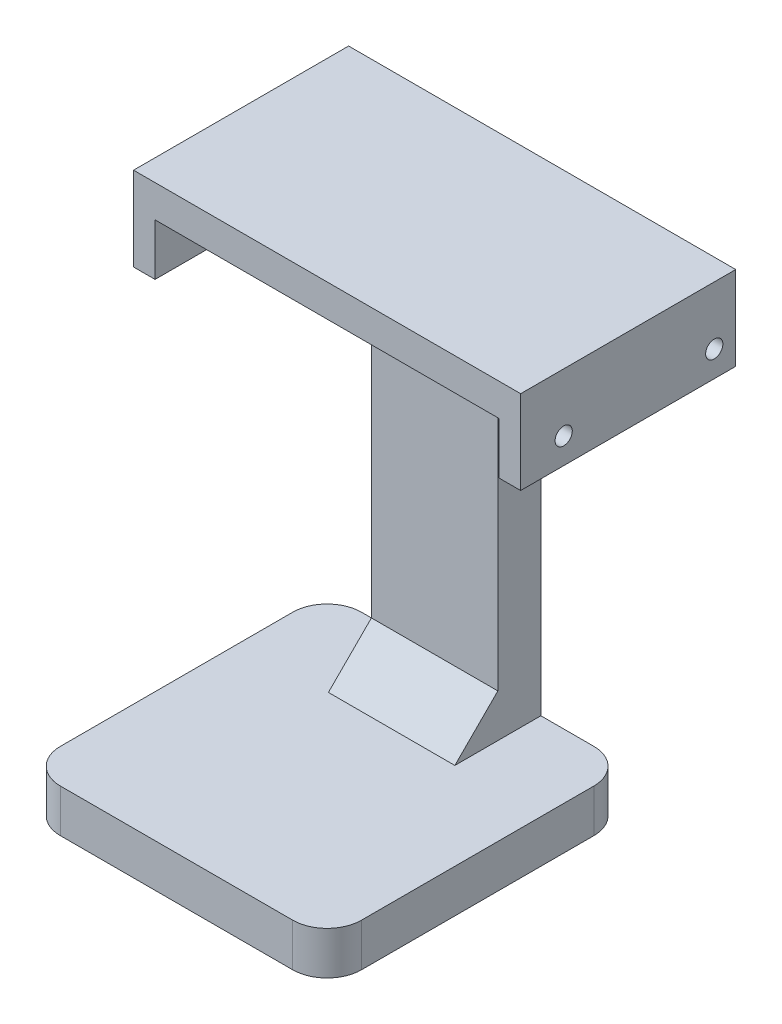
SolidWorks part; units mm, degrees
ref_plane "前视基准面" through (0, 0, 0) normal (0, 0, 1) x (1, 0, 0)
ref_plane "上视基准面" through (0, 0, 0) normal (0, 1, 0) x (1, 0, 0)
ref_plane "右视基准面" through (0, 0, 0) normal (1, 0, 0) x (0, 0, -1)
other "Configuration Table"
sketch "草图2" plane through (0, 0, 0) normal (0, 0, 1) x (1, 0, 0)
  line L0 (0, 48.4771) -> (0, -25.8756) construction
  line L1 (-45, 7.5) -> (45, 7.5)
  line L2 (45, 7.5) -> (45, -12)
  line L3 (45, -12) -> (40, -12)
  line L4 (40, -12) -> (40, 0)
  line L5 (40, 0) -> (14.7, 0)
  line L6 (14.7, 0) -> (14.7, -100)
  line L7 (14.7, -100) -> (-14.7, -100)
  line L8 (-14.7, 0) -> (-14.7, -100)
  line L9 (-40, 0) -> (-14.7, 0)
  line L10 (-40, -12) -> (-40, 0)
  line L11 (-45, -12) -> (-40, -12)
  line L12 (-45, 7.5) -> (-45, -12)
  dimension "D1" = 25.3
  dimension "D2" = 5
  dimension "D3" = 7.5
  dimension "D4" = 80
  dimension "D5" = 12
  dimension "D6" = 100
extrude "凸台-拉伸2" add sketch "草图2" along normal blind 35
sketch "草图3" plane through (0, 0, 0) normal (0, 1, 0) x (1, 0, 0)
  line L0 (45, 0) -> (-45, 0) construction
  line L1 (-35, -70) -> (35, -70)
  line L2 (-35, -70) -> (-35, 0)
  line L3 (-35, 0) -> (35, 0)
  line L4 (35, -70) -> (35, 0)
  line L5 (0, 20.1328) -> (0, -83.9717) construction
  dimension "D1" = 70
  dimension "D2" = 70
extrude "凸台-拉伸3" add sketch "草图3" along normal blind 10 from surface at -100 starting at face at (0, -100, 17.5)
sketch "草图4" plane through (0, 0, 0) normal (0, 0, 1) x (1, 0, 0)
  line L1 (-14.7, -90) -> (14.7, -90)
  line L2 (-14.7, -90) -> (-14.7, 0)
  line L3 (-14.7, 0) -> (14.7, 0)
  line L4 (14.7, -90) -> (14.7, 0)
extrude "切除-拉伸1" cut sketch "草图4" against normal blind 25 from surface at 35 starting at face at (0, -17.75, 35)
chamfer "倒角1" distance 10 angle 45 2 edges at (0, -90, 10) (0, 0, 10)
sketch "草图5" plane through (0, 0, 0) normal (0, 0, 1) x (1, 0, 0)
  line L0 (40, -12) -> (45, -12) construction
  line L1 (40, 0) -> (40, -12) construction
  line L2 (-40, -12) -> (-40, 0) construction
  line L3 (-45, -12) -> (-40, -12) construction
  line L4 (-45, 7.5) -> (-45, -12) construction
  line L5 (45, 7.5) -> (-45, 7.5) construction
  line L6 (45, -12) -> (45, 7.5) construction
  line L7 (40, -12) -> (45, -12)
  line L8 (40, 0) -> (40, -12)
  line L9 (-40, -12) -> (-40, 0)
  line L10 (-45, -12) -> (-40, -12)
  line L11 (-45, 7.5) -> (-45, -12)
  line L12 (45, 7.5) -> (-45, 7.5)
  line L13 (45, -12) -> (45, 7.5)
  line L14 (40, 0) -> (-40, 0)
extrude "凸台-拉伸4" add sketch "草图5" against normal blind 15
chamfer "倒角2" distance 5 angle 45 1 edges at (0, 0, 0)
sketch "草图6" plane through (0, 0, 0) normal (1, 0, 0) x (0, 0, -1)
  circle A0 centre (10, -6) radius 2
  circle A1 centre (-25, -6) radius 2
  dimension "D2" = 4
  dimension "D1" = 6
  dimension "D3" = 10
  dimension "D4" = 25
extrude "切除-拉伸2" cut sketch "草图6" against normal through all both and the other way through all
fillet "圆角2" radius 8 4 edges at (35, -95, 0) (35, -95, 70) (-35, -95, 0) (-35, -95, 70)
